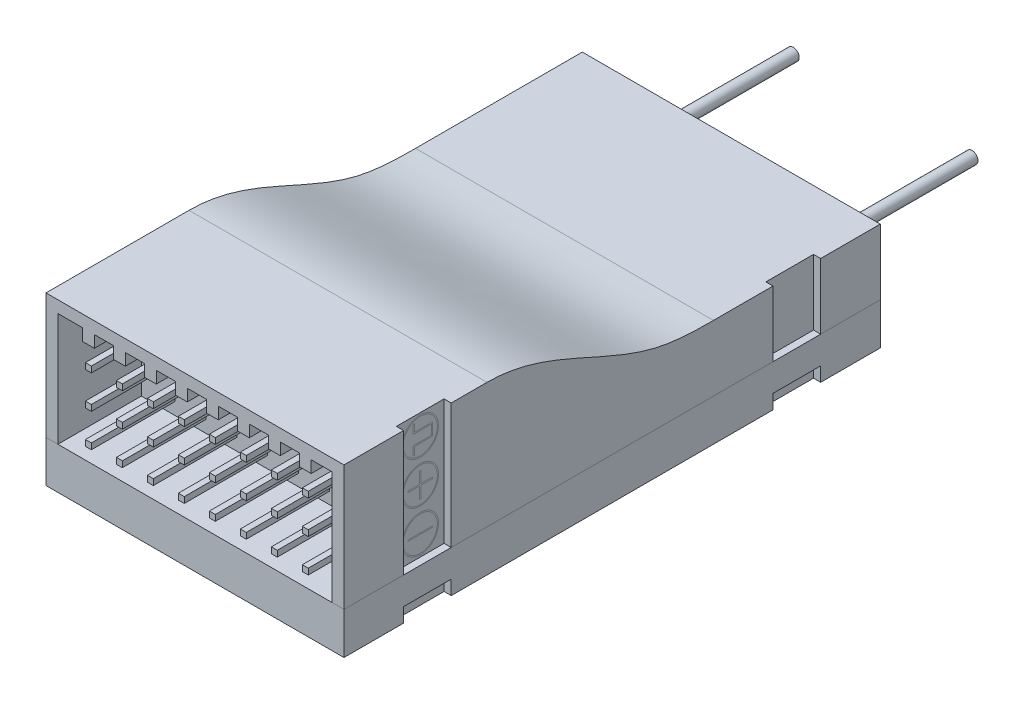
SolidWorks part; units mm, degrees
ref_plane "Front Plane" through (0, 0, 0) normal (0, 0, 1) x (1, 0, 0)
ref_plane "Top Plane" through (0, 0, 0) normal (0, 1, 0) x (1, 0, 0)
ref_plane "Right Plane" through (0, 0, 0) normal (1, 0, 0) x (0, 0, -1)
sketch "Sketch1" plane through (0, 0, 0) normal (0, 1, 0) x (1, 0, 0)
  line L1 (-12.5, -22.5) -> (12.5, -22.5)
  line L2 (-12.5, -22.5) -> (-12.5, 22.5)
  line L3 (-12.5, 22.5) -> (12.5, 22.5)
  line L4 (12.5, -22.5) -> (12.5, 22.5)
  line L5 (0, 22.5) -> (0, -22.5) construction
  line L6 (-12.5, 0) -> (12.5, 0) construction
  point P0 (0, 0)
  dimension "D1" = 45
  dimension "D2" = 25
extrude "Boss-Extrude1" add sketch "Sketch1" along normal blind 14
sketch "Sketch2" plane through (12.5, 0, 0) normal (1, 0, 0) x (0, 0, -1)
  line L0 (-22.5, 14) -> (22.5, 14) construction
  line L1 (8.5, 9) -> (22.5, 9)
  line L2 (-22.5, 0) -> (22.5, 0) construction
  line L3 (22.5, 14) -> (22.5, 0) construction
  line L4 (-10.5, 14) -> (-22.5, 14)
  line L5 (-22.5, 14) -> (-22.5, 21.1567)
  line L6 (-22.5, 21.1567) -> (22.5, 21.1567)
  line L7 (22.5, 21.1567) -> (22.5, 9)
  spline S0 degree 3 poles (-10.5, 14) (-9.1818, 14) (-4.1697, 13.0675) (1.8019, 9.209) (6.8321, 9) (8.5, 9) knots 0 0 0 0 0.196744 0.771521 1 1 1 1
  dimension "D1" = 9
  dimension "D2" = 12
  dimension "D3" = 14
  dimension "D4" = 7.1567
extrude "Cut-Extrude1" cut sketch "Sketch2" against normal through all and the other way through all
sketch "Sketch3" plane through (0, 0, -22.5) normal (0, 0, -1) x (-1, 0, 0)
  line L0 (-12.5, 0) -> (12.5, 0) construction
  line L1 (7.5, 5) -> (-7.5, 5) construction
  circle A0 centre (-7.5, 5) radius 0.5
  circle A1 centre (7.5, 5) radius 0.5
  point P6 (0, 0)
  point P7 (0, 5)
  dimension "D1" = 15
  dimension "D3" = 1
  dimension "D2" = 5
extrude "Boss-Extrude2" add sketch "Sketch3" along normal blind 12.7
ref_plane "Plane1" through (0, 3.5, 0) normal (0, -1, 0) x (-1, 0, 0)
split line "Split Line1"
sketch "Sketch4" plane through (0, 0, 0) normal (0, -1, 0) x (1, 0, 0)
  line L0 (12.5, 22.5) -> (12.5, -22.5) construction
  line L1 (12.5, 17.5) -> (11.9, 17.5)
  line L2 (12.5, 17.5) -> (12.5, 13.5)
  line L3 (12.5, 13.5) -> (11.9, 13.5)
  line L4 (11.9, 17.5) -> (11.9, 13.5)
  line L5 (7.7001, 0) -> (-7.7001, 0) construction
  line L10 (11.9, -17.5) -> (11.9, -13.5)
  line L11 (12.5, -13.5) -> (11.9, -13.5)
  line L12 (12.5, -17.5) -> (12.5, -13.5)
  line L13 (12.5, -17.5) -> (11.9, -17.5)
  line L14 (0, -7.7001) -> (0, 7.7001) construction
  line L15 (-12.5, -17.5) -> (-11.9, -17.5)
  line L16 (-12.5, -17.5) -> (-12.5, -13.5)
  line L17 (-12.5, -13.5) -> (-11.9, -13.5)
  line L18 (-11.9, -17.5) -> (-11.9, -13.5)
  line L19 (-11.9, 17.5) -> (-11.9, 13.5)
  line L20 (-12.5, 13.5) -> (-11.9, 13.5)
  line L21 (-12.5, 17.5) -> (-12.5, 13.5)
  line L22 (-12.5, 17.5) -> (-11.9, 17.5)
  dimension "D1" = 0.6
  dimension "D2" = 4
  dimension "D3" = 5
extrude "Cut-Extrude2" cut sketch "Sketch4" against normal blind 1.2
sketch "Sketch5" plane through (0, 0, 22.5) normal (0, 0, 1) x (1, 0, 0)
  line L8 (12.5, 3.5) -> (-12.5, 3.5) construction
  line L9 (11.5, 3.5) -> (-11.5, 3.5)
  line L12 (-11.5, 4.5) -> (11.5, 4.5)
  line L13 (11.5, 4.5) -> (11.5, 13)
  line L14 (11.5, 13) -> (-11.5, 13)
  line L15 (-11.5, 13) -> (-11.5, 4.5)
  line L17 (11.5, 3.5) -> (11.5, 13)
  line L18 (11.5, 13) -> (-11.5, 13)
  line L19 (-11.5, 13) -> (-11.5, 3.5)
  dimension "D1" = 1
extrude "Cut-Extrude3" cut sketch "Sketch5" against normal blind 7
sketch "Sketch6" plane through (0, 0, 22.5) normal (0, 0, 1) x (1, 0, 0)
  line L0 (-11.5, 13) -> (11.5, 13) construction
  line L1 (-6.8444, 13) -> (-6.8444, 12)
  line L2 (-9.4444, 13) -> (-8.4444, 13)
  line L3 (-9.4444, 13) -> (-9.4444, 12)
  line L4 (-9.4444, 12) -> (-8.4444, 12)
  line L5 (-8.4444, 13) -> (-8.4444, 12)
  line L6 (-6.8444, 13) -> (-5.8444, 13)
  line L7 (-5.8444, 13) -> (-5.8444, 12)
  line L8 (-6.8444, 12) -> (-5.8444, 12)
  line L9 (-4.2444, 13) -> (-4.2444, 12)
  line L10 (-4.2444, 13) -> (-3.2444, 13)
  line L11 (-3.2444, 13) -> (-3.2444, 12)
  line L12 (-4.2444, 12) -> (-3.2444, 12)
  line L13 (-1.6444, 13) -> (-1.6444, 12)
  line L14 (-1.6444, 13) -> (-0.6444, 13)
  line L15 (-0.6444, 13) -> (-0.6444, 12)
  line L16 (-1.6444, 12) -> (-0.6444, 12)
  line L17 (0.9556, 13) -> (0.9556, 12)
  line L18 (0.9556, 13) -> (1.9556, 13)
  line L19 (1.9556, 13) -> (1.9556, 12)
  line L20 (0.9556, 12) -> (1.9556, 12)
  line L21 (3.5556, 13) -> (3.5556, 12)
  line L22 (3.5556, 13) -> (4.5556, 13)
  line L23 (4.5556, 13) -> (4.5556, 12)
  line L24 (3.5556, 12) -> (4.5556, 12)
  line L25 (6.1556, 13) -> (6.1556, 12)
  line L26 (6.1556, 13) -> (7.1556, 13)
  line L27 (7.1556, 13) -> (7.1556, 12)
  line L28 (6.1556, 12) -> (7.1556, 12)
  line L29 (8.7556, 13) -> (8.7556, 12)
  line L30 (8.7556, 13) -> (9.7556, 13)
  line L31 (9.7556, 13) -> (9.7556, 12)
  line L32 (8.7556, 12) -> (9.7556, 12)
  line L33 (-9.4444, 13) -> (-6.8444, 13) construction
  point P4 (-8.9444, 13)
  point P5 (-6.3889, 13)
  point P6 (-3.8333, 13)
  point P7 (-1.2778, 13)
  point P8 (1.2778, 13)
  point P9 (3.8333, 13)
  point P10 (6.3889, 13)
  point P11 (8.9444, 13)
  point P17 (-8.9444, 12)
  point P19 (-3.8489, 13)
  point P20 (-1.3089, 13)
  point P21 (1.2311, 13)
  point P22 (3.7711, 13)
  point P23 (6.3111, 13)
  point P24 (8.8511, 13)
  point P25 (11.3911, 13)
  dimension "D1" = 1
  dimension "D4" = 2.6
  dimension "D2" = 8
  dimension "D3" = 8
sketch "Sketch8" plane through (12.5, 0, 0) normal (1, 0, 0) x (0, 0, -1)
  line L0 (22.5, 3.5) -> (-22.5, 3.5) construction
  line L1 (-13.5, 3.5) -> (-17.5, 3.5)
  line L2 (-13.5, 3.5) -> (-13.5, 14)
  line L3 (-13.5, 14) -> (-17.5, 14)
  line L4 (-17.5, 3.5) -> (-17.5, 14)
  line L5 (-13.5, 1.2) -> (-13.5, 0) construction
  line L6 (-17.5, 1.2) -> (-17.5, 0) construction
  line L7 (-22.5, 14) -> (-10.5, 14) construction
  line L8 (22.5, 9) -> (8.5, 9) construction
  line L9 (13.5, 3.5) -> (17.5, 3.5)
  line L10 (13.5, 3.5) -> (13.5, 9)
  line L11 (13.5, 9) -> (17.5, 9)
  line L12 (17.5, 3.5) -> (17.5, 9)
  line L13 (17.5, 1.2) -> (17.5, 0) construction
  line L14 (13.5, 1.2) -> (13.5, 0) construction
extrude "Cut-Extrude4" cut sketch "Sketch8" against normal up to surface (24.4 mm away)
sketch "Sketch9" plane through (11.9, 0, 0) normal (1, 0, 0) x (0, 0, -1)
  line L0 (-17.5, 3.5) -> (-13.5, 3.5) construction
  line L1 (-15.5, 18.9258) -> (-15.5, 3.5) construction
  line L2 (-15.9847, 12.7056) -> (-16.0863, 12.7056)
  line L3 (-15.4492, 11.8812) -> (-16.0863, 11.8812)
  line L5 (-17.5, 3.5) -> (-13.5, 3.5) construction
  line L6 (-17.5, 14) -> (-17.5, 3.5) construction
  line L7 (-15.5, 12.2934) -> (-15.5, 8.75) construction
  line L8 (-15.5, 8.75) -> (-15.5, 5.2066) construction
  line L9 (-15.9847, 12.8072) -> (-15.9847, 13.4361)
  line L10 (-16.5106, 5.1558) -> (-14.4894, 5.1558)
  line L11 (-16.5106, 5.1558) -> (-16.5106, 5.2574)
  line L12 (-16.5106, 5.2574) -> (-14.4894, 5.2574)
  line L13 (-14.4894, 5.1558) -> (-14.4894, 5.2574)
  line L14 (-15.5, 5.2574) -> (-15.5, 5.1558) construction
  line L15 (-16.5106, 5.2066) -> (-14.4894, 5.2066) construction
  line L16 (-16.5332, 8.6865) -> (-15.5635, 8.6865)
  line L17 (-16.5332, 8.6865) -> (-16.5332, 8.8135)
  line L18 (-16.5332, 8.8135) -> (-15.5635, 8.8135)
  line L19 (-14.4668, 8.6865) -> (-14.4668, 8.8135)
  line L20 (-15.5, 8.8135) -> (-15.5, 8.6865) construction
  line L21 (-16.5332, 8.75) -> (-14.4668, 8.75) construction
  line L22 (-15.5635, 7.7168) -> (-15.4365, 7.7168)
  line L23 (-15.5635, 7.7168) -> (-15.5635, 8.6865)
  line L24 (-15.5635, 9.7832) -> (-15.4365, 9.7832)
  line L25 (-15.4365, 7.7168) -> (-15.4365, 8.6865)
  line L26 (-15.5, 9.7832) -> (-15.5, 7.7168) construction
  line L27 (-15.5635, 8.75) -> (-15.4365, 8.75) construction
  line L28 (-16.0863, 11.1508) -> (-15.9847, 11.1508)
  line L29 (-16.0863, 11.1508) -> (-16.0863, 11.8812)
  line L30 (-16.0863, 13.4361) -> (-15.9847, 13.4361)
  line L31 (-15.9847, 11.1508) -> (-15.9847, 11.7796)
  line L32 (-16.0355, 13.4361) -> (-16.0355, 11.1508) construction
  line L33 (-15.5508, 12.2934) -> (-15.4492, 12.2934) construction
  line L34 (-15.9847, 12.7056) -> (-14.5551, 12.7056)
  line L36 (-15.4492, 11.8812) -> (-14.5551, 11.8812)
  line L37 (-14.5551, 12.7056) -> (-14.5551, 11.8812)
  line L38 (-15.9847, 12.8072) -> (-14.4535, 12.8072)
  line L40 (-15.9847, 11.7796) -> (-14.4535, 11.7796)
  line L41 (-14.4535, 12.8072) -> (-14.4535, 11.7796)
  line L42 (-16.0863, 12.7056) -> (-16.0863, 13.4361)
  line L43 (-15.5635, 8.8135) -> (-15.5635, 9.7832)
  line L44 (-15.4365, 8.8135) -> (-15.4365, 9.7832)
  line L45 (-15.4365, 8.6865) -> (-14.4668, 8.6865)
  line L46 (-15.4365, 8.8135) -> (-14.4668, 8.8135)
  circle A0 centre (-15.5, 5.2066) radius 1.5372
  circle A1 centre (-15.5, 8.75) radius 1.5372
  circle A2 centre (-15.5, 12.2934) radius 1.5372
  circle A3 centre (-15.5, 8.75) radius 1.4356
  circle A4 centre (-15.5, 12.2934) radius 1.4356
  circle A5 centre (-15.5, 5.2066) radius 1.4356
  point P6 (-15.5, 3.5)
  point P7 (-15.5, 11.375)
  point P14 (-15.5, 12.2934)
  point P15 (-15.5, 5.2066)
  point P25 (-17.5, 8.75)
  point P45 (-14.4535, 12.2934)
  point P46 (-14.5551, 12.2934)
  dimension "D2" = 0.1016
  dimension "D3" = 0.1016
  dimension "D4" = 0.1016
  dimension "D5" = 0.127
  dimension "D6" = 0.127
  dimension "D7" = 0.1016
  dimension "D1" = 0.1016
split line "Split Line2"
extrude "Boss-Extrude4" add sketch "Sketch6" against normal up to next
sketch "Sketch7" plane through (0, 0, 22.5) normal (0, 0, 1) x (1, 0, 0)
  line L0 (-11.5, 3.5) -> (11.5, 3.5) construction
  line L1 (-9.1944, 5) -> (-8.6944, 5)
  line L2 (-9.1944, 5) -> (-9.1944, 4.5)
  line L3 (-9.1944, 4.5) -> (-8.6944, 4.5)
  line L4 (-8.6944, 5) -> (-8.6944, 4.5)
  line L5 (-6.5944, 5) -> (-6.5944, 4.5)
  line L6 (-6.5944, 5) -> (-6.0944, 5)
  line L7 (-6.0944, 5) -> (-6.0944, 4.5)
  line L8 (-6.5944, 4.5) -> (-6.0944, 4.5)
  line L9 (-3.9944, 5) -> (-3.9944, 4.5)
  line L10 (-3.9944, 5) -> (-3.4944, 5)
  line L11 (-3.4944, 5) -> (-3.4944, 4.5)
  line L12 (-3.9944, 4.5) -> (-3.4944, 4.5)
  line L13 (-1.3944, 5) -> (-1.3944, 4.5)
  line L14 (-1.3944, 5) -> (-0.8944, 5)
  line L15 (-0.8944, 5) -> (-0.8944, 4.5)
  line L16 (-1.3944, 4.5) -> (-0.8944, 4.5)
  line L17 (1.2056, 5) -> (1.2056, 4.5)
  line L18 (1.2056, 5) -> (1.7056, 5)
  line L19 (1.7056, 5) -> (1.7056, 4.5)
  line L20 (1.2056, 4.5) -> (1.7056, 4.5)
  line L21 (3.8056, 5) -> (3.8056, 4.5)
  line L22 (3.8056, 5) -> (4.3056, 5)
  line L23 (4.3056, 5) -> (4.3056, 4.5)
  line L24 (3.8056, 4.5) -> (4.3056, 4.5)
  line L25 (6.4056, 5) -> (6.4056, 4.5)
  line L26 (6.4056, 5) -> (6.9056, 5)
  line L27 (6.9056, 5) -> (6.9056, 4.5)
  line L28 (6.4056, 4.5) -> (6.9056, 4.5)
  line L29 (9.0056, 5) -> (9.0056, 4.5)
  line L30 (9.0056, 5) -> (9.5056, 5)
  line L31 (9.5056, 5) -> (9.5056, 4.5)
  line L32 (9.0056, 4.5) -> (9.5056, 4.5)
  line L33 (-9.1944, 5) -> (-6.5944, 5) construction
  line L34 (-9.1944, 7.794) -> (-8.6944, 7.794)
  line L35 (-9.1944, 7.794) -> (-9.1944, 7.294)
  line L36 (-9.1944, 7.294) -> (-8.6944, 7.294)
  line L37 (-8.6944, 7.794) -> (-8.6944, 7.294)
  line L38 (-6.5944, 7.794) -> (-6.5944, 7.294)
  line L39 (-6.5944, 7.794) -> (-6.0944, 7.794)
  line L40 (-6.0944, 7.794) -> (-6.0944, 7.294)
  line L41 (-6.5944, 7.294) -> (-6.0944, 7.294)
  line L42 (-3.9944, 7.794) -> (-3.9944, 7.294)
  line L43 (-3.9944, 7.794) -> (-3.4944, 7.794)
  line L44 (-3.4944, 7.794) -> (-3.4944, 7.294)
  line L45 (-3.9944, 7.294) -> (-3.4944, 7.294)
  line L46 (-1.3944, 7.794) -> (-1.3944, 7.294)
  line L47 (-1.3944, 7.794) -> (-0.8944, 7.794)
  line L48 (-0.8944, 7.794) -> (-0.8944, 7.294)
  line L49 (-1.3944, 7.294) -> (-0.8944, 7.294)
  line L50 (1.2056, 7.794) -> (1.2056, 7.294)
  line L51 (1.2056, 7.794) -> (1.7056, 7.794)
  line L52 (1.7056, 7.794) -> (1.7056, 7.294)
  line L53 (1.2056, 7.294) -> (1.7056, 7.294)
  line L54 (3.8056, 7.794) -> (3.8056, 7.294)
  line L55 (3.8056, 7.794) -> (4.3056, 7.794)
  line L56 (4.3056, 7.794) -> (4.3056, 7.294)
  line L57 (3.8056, 7.294) -> (4.3056, 7.294)
  line L58 (6.4056, 7.794) -> (6.4056, 7.294)
  line L59 (6.4056, 7.794) -> (6.9056, 7.794)
  line L60 (6.9056, 7.794) -> (6.9056, 7.294)
  line L61 (6.4056, 7.294) -> (6.9056, 7.294)
  line L62 (9.0056, 7.794) -> (9.0056, 7.294)
  line L63 (9.0056, 7.794) -> (9.5056, 7.794)
  line L64 (9.5056, 7.794) -> (9.5056, 7.294)
  line L65 (9.0056, 7.294) -> (9.5056, 7.294)
  line L66 (-9.1944, 10.588) -> (-8.6944, 10.588)
  line L67 (-9.1944, 10.588) -> (-9.1944, 10.088)
  line L68 (-9.1944, 10.088) -> (-8.6944, 10.088)
  line L69 (-8.6944, 10.588) -> (-8.6944, 10.088)
  line L70 (-6.5944, 10.588) -> (-6.5944, 10.088)
  line L71 (-6.5944, 10.588) -> (-6.0944, 10.588)
  line L72 (-6.0944, 10.588) -> (-6.0944, 10.088)
  line L73 (-6.5944, 10.088) -> (-6.0944, 10.088)
  line L74 (-3.9944, 10.588) -> (-3.9944, 10.088)
  line L75 (-3.9944, 10.588) -> (-3.4944, 10.588)
  line L76 (-3.4944, 10.588) -> (-3.4944, 10.088)
  line L77 (-3.9944, 10.088) -> (-3.4944, 10.088)
  line L78 (-1.3944, 10.588) -> (-1.3944, 10.088)
  line L79 (-1.3944, 10.588) -> (-0.8944, 10.588)
  line L80 (-0.8944, 10.588) -> (-0.8944, 10.088)
  line L81 (-1.3944, 10.088) -> (-0.8944, 10.088)
  line L82 (1.2056, 10.588) -> (1.2056, 10.088)
  line L83 (1.2056, 10.588) -> (1.7056, 10.588)
  line L84 (1.7056, 10.588) -> (1.7056, 10.088)
  line L85 (1.2056, 10.088) -> (1.7056, 10.088)
  line L86 (3.8056, 10.588) -> (3.8056, 10.088)
  line L87 (3.8056, 10.588) -> (4.3056, 10.588)
  line L88 (4.3056, 10.588) -> (4.3056, 10.088)
  line L89 (3.8056, 10.088) -> (4.3056, 10.088)
  line L90 (6.4056, 10.588) -> (6.4056, 10.088)
  line L91 (6.4056, 10.588) -> (6.9056, 10.588)
  line L92 (6.9056, 10.588) -> (6.9056, 10.088)
  line L93 (6.4056, 10.088) -> (6.9056, 10.088)
  line L94 (9.0056, 10.588) -> (9.0056, 10.088)
  line L95 (9.0056, 10.588) -> (9.5056, 10.588)
  line L96 (9.5056, 10.588) -> (9.5056, 10.088)
  line L97 (9.0056, 10.088) -> (9.5056, 10.088)
  line L98 (-9.1944, 5) -> (-9.1944, 7.794) construction
  point P4 (-8.9444, 4.5)
  dimension "D1" = 0.5
  dimension "D2" = 1
  dimension "D4" = 2.6
  dimension "D6" = 2.794
  dimension "D3" = 8
  dimension "D5" = 3
extrude "Boss-Extrude5" add sketch "Sketch7" against normal up to surface (7 mm away) up to face at (0.1383, 12.0278, 15.5)
other "SurfaceCut1" [suppressed]
mirror "Mirror9" [suppressed] about plane through (0, 0, 0) normal (1, 0, 0)
scale "Ölçek1" scale about centroid uniform scaling yes scale factor 0.5
equation "\"D2@Sketch9\"=\"D1@Sketch9\""
equation "\"D3@Sketch9\"=\"D2@Sketch9\""
equation "\"D4@Sketch9\"=\"D3@Sketch9\""
equation "\"D6@Sketch9\"=\"D5@Sketch9\""
equation "\"D7@Sketch9\"=\"D1@Sketch9\""
